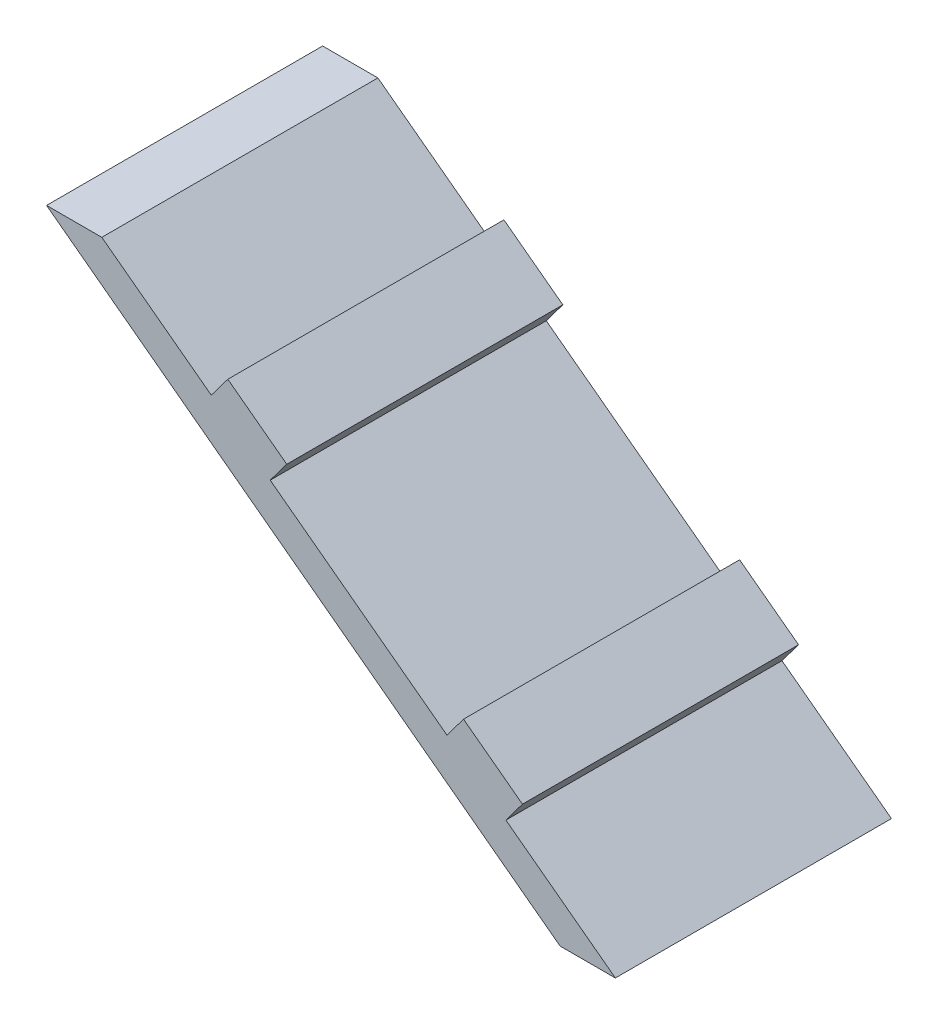
SolidWorks part; units mm, degrees
ref_plane "前视基准面" through (0, 0, 0) normal (0, 0, 1) x (1, 0, 0)
ref_plane "上视基准面" through (0, 0, 0) normal (0, 1, 0) x (1, 0, 0)
ref_plane "右视基准面" through (0, 0, 0) normal (1, 0, 0) x (0, 0, -1)
other "Configuration Table"
sketch "草图1" plane through (0, 0, 366) normal (0, 0, 1) x (1, 0, 0)
  line L0 (-87.0247, 495) -> (192, 286)
  line L1 (192, 286) -> (222.0247, 286)
  line L2 (222.0247, 286) -> (-57, 495)
  line L3 (-57, 495) -> (-87.0247, 495)
  line L4 (-42, 495) -> (-32, 495) construction
  line L5 (372, 286) -> (192, 286) construction
  line L6 (-372, 495) -> (-42, 495) construction
  line L7 (2.4754, 450.4507) -> (34.4902, 426.4704)
  line L8 (2.4754, 450.4507) -> (11.468, 462.4562)
  line L9 (34.4902, 426.4704) -> (43.4828, 438.476)
  line L10 (11.468, 462.4562) -> (43.4828, 438.476)
  line L11 (130.5345, 354.5296) -> (162.5493, 330.5493)
  line L12 (130.5345, 354.5296) -> (139.5271, 366.5351)
  line L13 (162.5493, 330.5493) -> (171.5419, 342.5548)
  line L14 (139.5271, 366.5351) -> (171.5419, 342.5548)
  line L15 (-32, 513) -> (-32, 495) construction
  line L16 (182, 268) -> (182, 286) construction
  point P8 (82.5123, 390.5)
  dimension "D1" = 18
  dimension "D2" = 25
  dimension "D3" = 10
  dimension "D4" = 60
  dimension "D5" = 60
  dimension "D6" = 40
  dimension "D7" = 15
extrude "凸台-拉伸1" add sketch "草图1" against normal up to surface (150 mm away) separate body contours L0 L1 L2 L3 | L10 L9 L7 L8 | L14 L13 L11 L12
